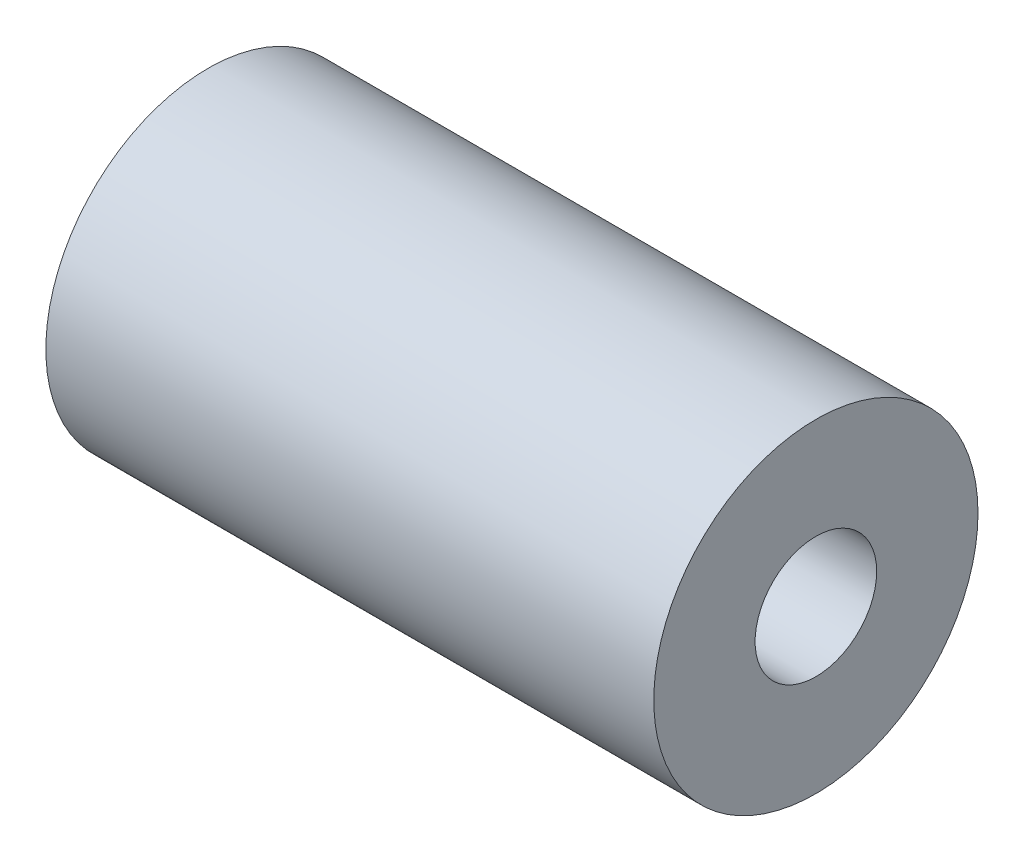
SolidWorks part; units mm, degrees
ref_plane "Front Plane" through (0, 0, 0) normal (0, 0, 1) x (1, 0, 0)
ref_plane "Top Plane" through (0, 0, 0) normal (0, 1, 0) x (1, 0, 0)
ref_plane "Right Plane" through (0, 0, 0) normal (1, 0, 0) x (0, 0, -1)
sketch "Sketch1" plane through (0, 0, 0) normal (1, 0, 0) x (0, 0, -1)
  circle A0 centre (0, 0) radius 1.5
  circle A1 centre (0, 0) radius 4
extrude "Boss-Extrude1" add sketch "Sketch1" along normal blind 15
